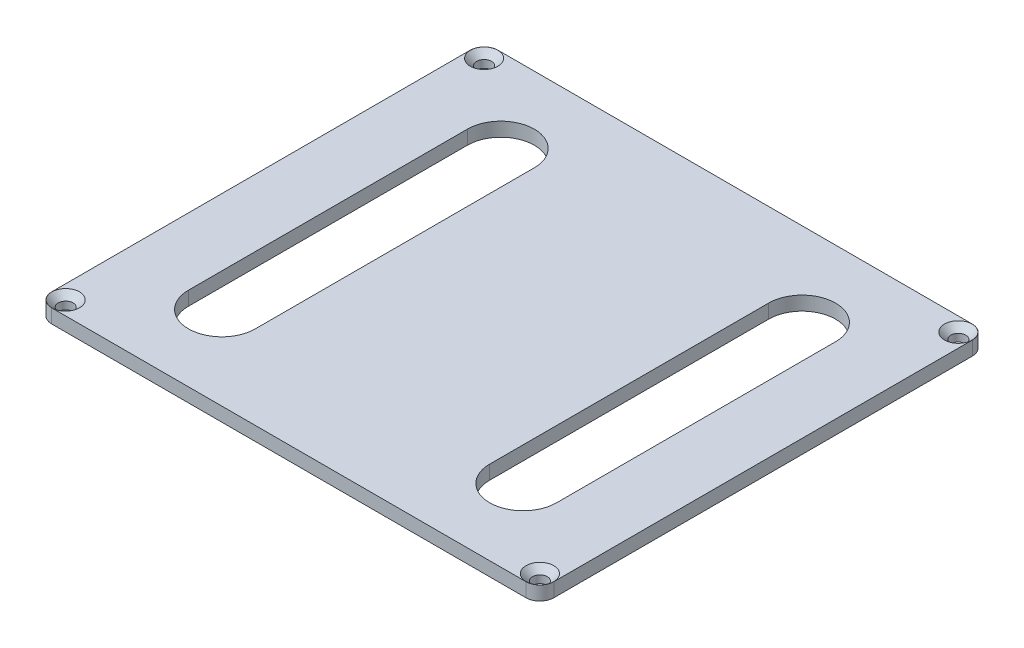
SolidWorks part; units mm, degrees
ref_plane "Front Plane" through (0, 0, 0) normal (0, 0, 1) x (1, 0, 0)
ref_plane "Top Plane" through (0, 0, 0) normal (0, 1, 0) x (1, 0, 0)
ref_plane "Right Plane" through (0, 0, 0) normal (1, 0, 0) x (0, 0, -1)
sketch "Sketch1" plane through (0, 0, 0) normal (0, 1, 0) x (1, 0, 0)
  line L1 (57.15, -50.8) -> (-57.15, -50.8)
  line L2 (57.15, -50.8) -> (57.15, 50.8)
  line L3 (57.15, 50.8) -> (-57.15, 50.8)
  line L4 (-57.15, -50.8) -> (-57.15, 50.8)
  line L5 (0, 50.8) -> (0, -50.8) construction
  line L6 (57.15, 0) -> (-57.15, 0) construction
  point P0 (0, 0)
  dimension "D1" = 114.3
  dimension "D2" = 101.6
extrude "Boss-Extrude1" add sketch "Sketch1" along normal blind 3.175
fillet "Fillet1" radius 3.175 4 edges at (-57.15, 1.5875, 50.8) (-57.15, 1.5875, -50.8) (57.15, 1.5875, -50.8) (57.15, 1.5875, 50.8)
hole_wizard "CSK for M3 Flat Head Machine Screw1" positions "Sketch2" profile "Sketch3" countersink size "M3" standard "ANSI Metric"
sketch "Sketch2" plane through (0, 3.175, 0) normal (0, 1, 0) x (1, 0, 0)
  point P0 (53.975, -47.625)
  point P3 (53.975, 47.625)
  point P6 (-53.975, 47.625)
  point P9 (-53.975, -47.625)
sketch "Sketch3" plane through (53.975, 3.175, 47.625) normal (1, 0, 0) x (0, 0, 1)
  line L0 (0, 0) -> (0, 8.8955)
  line L1 (0, 8.8955) -> (1.7, 7.874)
  line L2 (1.7, 7.874) -> (1.7, 1.45)
  line L3 (1.7, 1.45) -> (3.15, 0)
  line L5 (3.15, 0) -> (0, 0)
  line L6 (-1.7, 1.45) -> (-3.15, 0) construction
  line L10 (0, 8.8955) -> (-1.7, 7.874) construction
  line L11 (0, -6.35) -> (0, 107.95) construction
  dimension "Hole Dia." = 3.4
  dimension "Hole Depth" = 7.874
  dimension "Near C'Sink Dia." = 6.3
  dimension "Near C'Sink Angle" = 90
  dimension "Drill Angle" = 118
sketch "Sketch4" plane through (0, 3.175, 0) normal (0, 1, 0) x (1, 0, 0)
  line L0 (-34.29, -31.75) -> (-34.29, 31.75) construction
  line L1 (-41.91, -31.75) -> (-41.91, 31.75)
  line L2 (-26.67, -31.75) -> (-26.67, 31.75)
  line L3 (-57.15, 47.625) -> (-57.15, -47.625) construction
  line L4 (0, -1.7463) -> (0, 1.7463) construction
  line L5 (34.29, -31.75) -> (34.29, 31.75) construction
  line L6 (41.91, -31.75) -> (41.91, 31.75)
  line L7 (26.67, -31.75) -> (26.67, 31.75)
  arc A0 (-41.91, -31.75) -> (-26.67, -31.75) centre (-34.29, -31.75) ccw
  arc A1 (-26.67, 31.75) -> (-41.91, 31.75) centre (-34.29, 31.75) ccw
  arc A2 (41.91, -31.75) -> (26.67, -31.75) centre (34.29, -31.75) cw
  arc A3 (26.67, 31.75) -> (41.91, 31.75) centre (34.29, 31.75) cw
  point P2 (-34.29, 0)
  point P9 (-57.15, 0)
  point P14 (34.29, 0)
  dimension "D2" = 7.62
  dimension "D1" = 15.24
  dimension "D3" = 63.5
extrude "Cut-Extrude1" cut sketch "Sketch4" against normal through all
